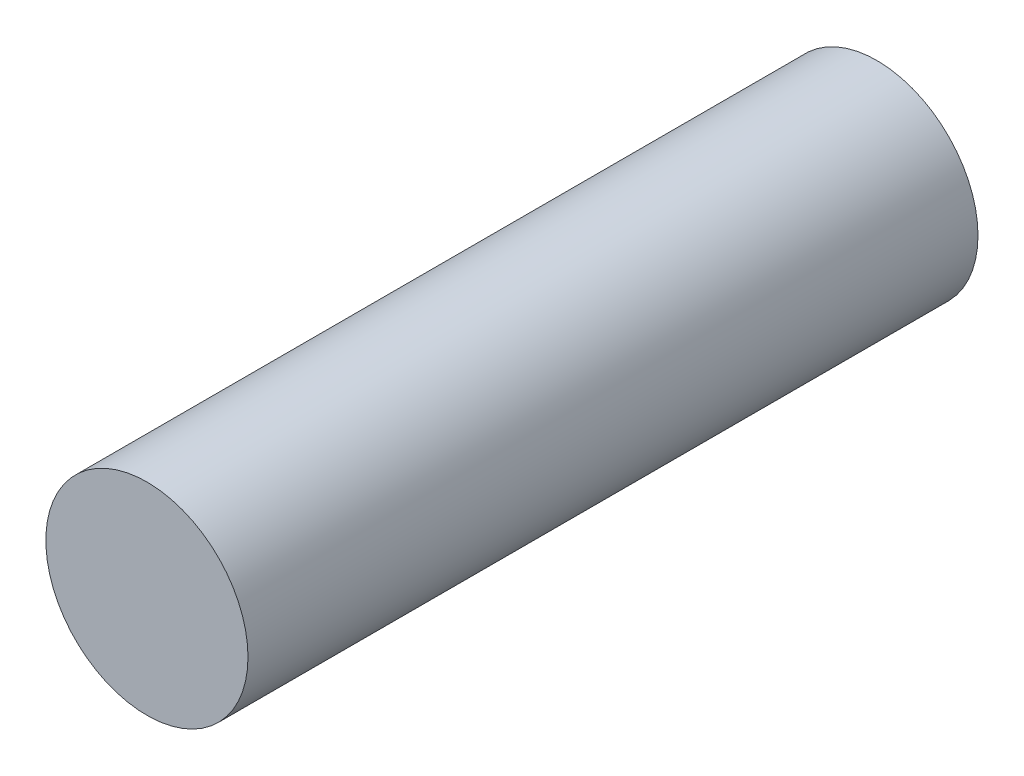
SolidWorks part; units mm, degrees
ref_plane "Alzado" through (0, 0, 0) normal (0, 0, 1) x (1, 0, 0)
ref_plane "Planta" through (0, 0, 0) normal (0, 1, 0) x (1, 0, 0)
ref_plane "Vista lateral" through (0, 0, 0) normal (1, 0, 0) x (0, 0, -1)
sketch "Croquis1" plane through (0, 0, 0) normal (0, 0, 1) x (1, 0, 0)
  circle A0 centre (0, 0) radius 9
  dimension "D1" = 18
extrude "Saliente-Extruir1" add sketch "Croquis1" along normal blind 65
